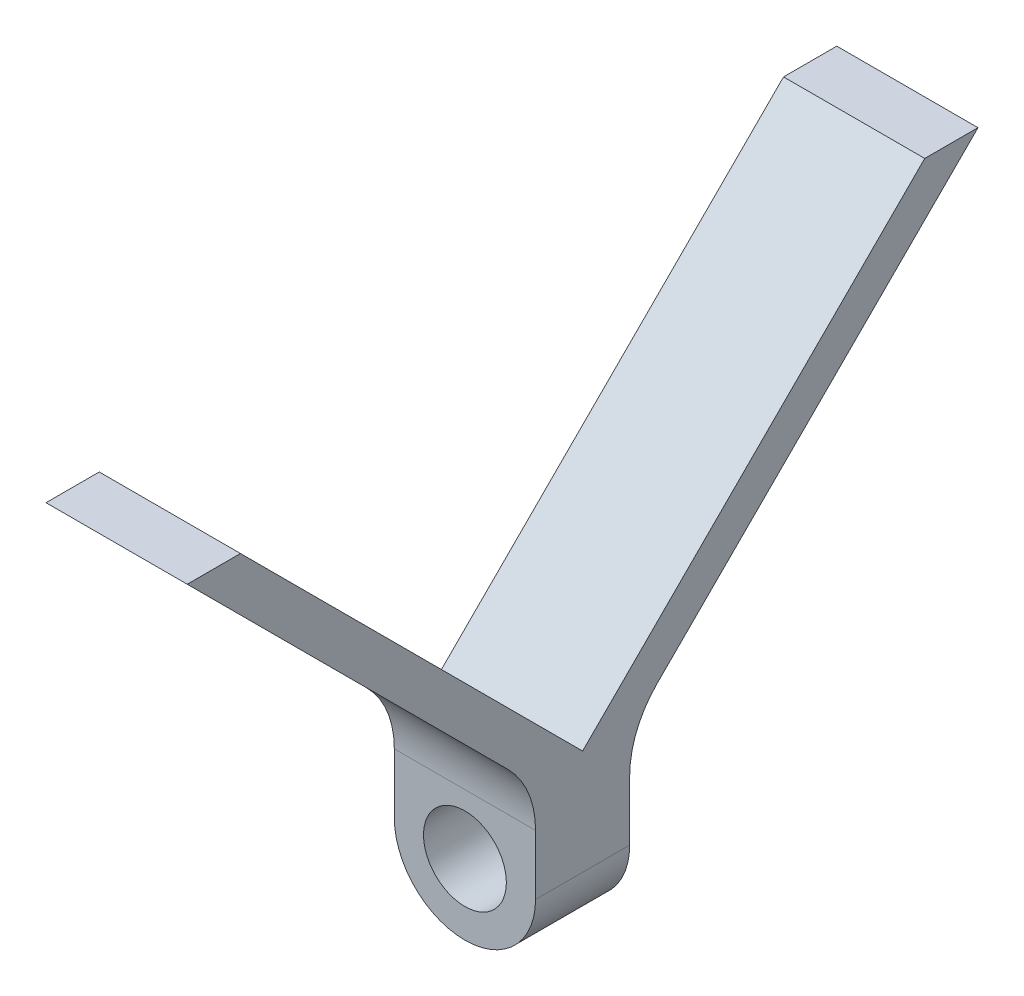
SolidWorks part; units mm, degrees
ref_plane "Front Plane" through (0, 0, 0) normal (0, 0, 1) x (1, 0, 0)
ref_plane "Top Plane" through (0, 0, 0) normal (0, 1, 0) x (1, 0, 0)
ref_plane "Right Plane" through (0, 0, 0) normal (1, 0, 0) x (0, 0, -1)
sketch "Sketch1" plane through (0, 0, 0) normal (0, 0, 1) x (1, 0, 0)
  line L0 (-3.75, 0) -> (-3.75, 3.75)
  line L1 (-3.75, 3.75) -> (3.75, 3.75)
  line L2 (3.75, 3.75) -> (3.75, 0)
  arc A0 (-3.75, 0) -> (3.75, 0) centre (0, 0) ccw
  dimension "D1" = 7.5
extrude "Boss-Extrude1" add sketch "Sketch1" along normal mid plane 5
sketch "Sketch3" plane through (0, 0, 0) normal (1, 0, 0) x (0, 0, -1)
  line L0 (0, 0) -> (0, 3.75) construction
  line L1 (-2.5, 3.75) -> (2.5, 3.75) construction
  line L5 (0, 2.75) -> (21, 23.75)
  line L6 (21, 23.75) -> (-21, 23.75)
  line L7 (-21, 23.75) -> (0, 2.75)
  dimension "D1" = 1
  dimension "D2" = 90
  dimension "D3" = 20
extrude "Boss-Extrude2" add sketch "Sketch3" along normal up to surface and the other way up to surface up to face at (3.75, 1.875, 0) other way up to face at (-3.75, 1.875, 0)
sketch "Sketch4" plane through (3.75, 0, 0) normal (1, 0, 0) x (0, 0, -1)
  line L0 (-18.1716, 23.75) -> (0, 5.5784)
  line L1 (-21, 23.75) -> (21, 23.75) construction
  line L2 (0, 5.5784) -> (18.1716, 23.75)
  line L3 (18.1716, 23.75) -> (-18.1716, 23.75)
  line L4 (0, 0) -> (0, 23.75) construction
  line L5 (21, 23.75) -> (1, 3.75) construction
  line L6 (-1, 3.75) -> (-21, 23.75) construction
  dimension "D1" = 2
extrude "Cut-Extrude2" cut sketch "Sketch4" along normal through all and the other way through all
sketch "Sketch5" plane through (3.75, 0, 0) normal (1, 0, 0) x (0, 0, -1)
  line L0 (-2.5, 3.75) -> (-2.5, 5.25)
  line L1 (-1, 3.75) -> (-21, 23.75) construction
  line L2 (-2.5, 5.25) -> (2.5, 5.25)
  line L3 (21, 23.75) -> (1, 3.75) construction
  line L4 (2.5, 5.25) -> (2.5, 3.75)
  line L5 (2.5, 3.75) -> (-2.5, 3.75)
extrude "Boss-Extrude3" add sketch "Sketch5" against normal up to surface (7.5 mm away) up to face at (-3.75, 10.5071, 0)
sketch "Sketch6" plane through (0, 0, 2.5) normal (0, 0, 1) x (1, 0, 0)
  circle A0 centre (0, 0) radius 2.2
  dimension "D1" = 4.4
extrude "Cut-Extrude4" cut sketch "Sketch6" against normal blind 10
fillet "Fillet1" radius 5 2 edges at (0, 5.25, -2.5) (0, 5.25, 2.5)
